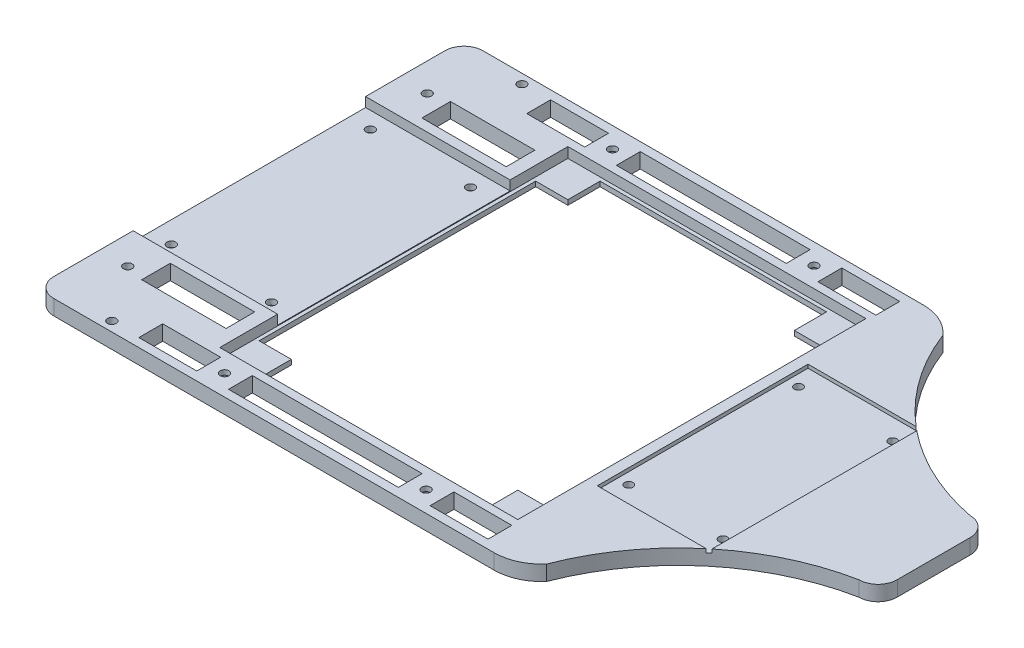
SolidWorks part; units mm, degrees
ref_plane "Alzado" through (0, 0, 0) normal (0, 0, 1) x (1, 0, 0)
ref_plane "Planta" through (0, 0, 0) normal (0, 1, 0) x (1, 0, 0)
ref_plane "Vista lateral" through (0, 0, 0) normal (1, 0, 0) x (0, 0, -1)
sketch "Croquis1" plane through (0, 0, 0) normal (0, 1, 0) x (1, 0, 0)
  line L1 (-363.842, 247.1559) -> (108.158, 247.1559) construction
  line L2 (98.4842, 266.9705) -> (494.4842, 266.9705) construction
  line L11 (99, 267.5) -> (495, 267.5) construction
  line L12 (0, 0) -> (200, 0)
  line L22 (0, 90) -> (105.7, 90)
  line L23 (105.7, 90) -> (105.7, 83.1308) construction
  line L24 (105.7, 83.1308) -> (120.7782, 83.1308) construction
  line L25 (200, 0) -> (200, 15.2)
  line L26 (200, 15.2) -> (191.999, 15.2) construction
  line L27 (191.999, 15.2) -> (191.999, 23.325) construction
  line L29 (0, 0) -> (-110.4, 0)
  line L30 (0, 90) -> (-79, 90)
  line L31 (-110.4, 0) -> (-110.4, 13.12)
  line L32 (-86.9998, 82.0528) -> (-86.9998, 41.494)
  arc A0 (105.7, 90) -> (120.7782, 83.1308) centre (105.672, 69.9553) cw
  arc A1 (200, 15.2) -> (191.999, 23.325) centre (192.001, 15.325) ccw
  arc A2 (120.7782, 83.1308) -> (191.999, 23.325) centre (210.4273, 117.5809) ccw
  arc A3 (-79, 90) -> (-86.9998, 82.0528) centre (-79, 82) ccw
  arc A4 (-110.4, 13.12) -> (-102.3535, 21.1199) centre (-102.4, 13.12) cw
  arc A5 (-102.3535, 21.1199) -> (-86.9998, 41.494) centre (-113.1395, 45.2203) ccw
  dimension "D6" = 20.0447
  dimension "D10" = 8
  dimension "D11" = 96.0405
  dimension "D15" = 8
  dimension "D17" = 8
  dimension "D19" = 26.4039
  dimension "D22" = 45.2203
  dimension "D1" = 90
  dimension "D2" = 200
  dimension "D3" = 105.7
  dimension "D4" = 6.8692
  dimension "D5" = 15.0782
  dimension "D7" = 15.2
  dimension "D8" = 8.001
  dimension "D9" = 8.125
  dimension "D12" = 105.7
  dimension "D13" = 310.4
  dimension "D14" = 79
  dimension "D16" = 13.12
  dimension "D18" = 40.5588
  dimension "D20" = 90
  dimension "D21" = 286.9998
extrude "Saliente-Extruir1" add sketch "Croquis1" along normal blind 6.35
mirror "Simetría2" about plane through (0, 6.35, 0) normal (0, 0, -1) of bodies 104
sketch "Croquis2" plane through (0, 6.35, 0) normal (0, 1, 0) x (1, 0, 0)
  line L0 (200, 0) -> (-110.4, 0) construction
  line L1 (200, -15.2) -> (200, 15.2) construction
  line L2 (-110.4, 13.12) -> (-110.4, -13.12) construction
  line L3 (0, 90) -> (-86.9348, 90) construction
  line L4 (105.7, 90) -> (-79, 90) construction
  line L5 (-17.875, 81.35) -> (70.325, 81.35) construction
  line L6 (0, 90) -> (0, 0) construction
  line L7 (-14.225, 81.35) -> (-1.9998, 81.35) construction
  line L8 (13.35, -90) -> (13.35, 90) construction
  line L9 (105.7, -90) -> (-79, -90) construction
  line L10 (-17.875, -81.35) -> (70.325, -81.35) construction
  line L15 (26.225, -81.35) -> (26.225, -54.2886) construction
  line L16 (-1.9998, -86.35) -> (61.85, -86.35)
  line L17 (-1.9998, -86.35) -> (-1.9998, -76.35)
  line L18 (-1.9998, -76.35) -> (61.85, -76.35)
  line L19 (61.85, -86.35) -> (61.85, -76.35)
  line L20 (-86.9998, -82.0528) -> (-86.9998, -41.494) construction
  line L21 (-46.9998, -76.35) -> (-22.7, -76.35)
  line L22 (-46.9998, -76.35) -> (-46.9998, -86.35)
  line L23 (-46.9998, -86.35) -> (-22.7, -86.35)
  line L24 (-22.7, -76.35) -> (-22.7, -86.35)
  line L25 (99.4498, -86.35) -> (75.15, -86.35)
  line L26 (75.15, -76.35) -> (75.15, -86.35)
  line L27 (99.4498, -76.35) -> (75.15, -76.35)
  line L28 (99.4498, -76.35) -> (99.4498, -86.35)
  line L29 (-46.9998, 86.35) -> (-22.7, 86.35)
  line L30 (-22.7, 76.35) -> (-22.7, 86.35)
  line L31 (-46.9998, 76.35) -> (-22.7, 76.35)
  line L32 (-46.9998, 76.35) -> (-46.9998, 86.35)
  line L33 (-1.9998, 76.35) -> (61.85, 76.35)
  line L34 (61.85, 86.35) -> (61.85, 76.35)
  line L35 (-1.9998, 86.35) -> (61.85, 86.35)
  line L36 (-1.9998, 86.35) -> (-1.9998, 76.35)
  line L37 (99.4498, 76.35) -> (99.4498, 86.35)
  line L38 (99.4498, 76.35) -> (75.15, 76.35)
  line L39 (75.15, 76.35) -> (75.15, 86.35)
  line L40 (99.4498, 86.35) -> (75.15, 86.35)
  circle A0 centre (68.5, 81.35) radius 1.825
  circle A1 centre (-16.05, 81.35) radius 1.825
  circle A2 centre (68.5, -81.35) radius 1.825
  circle A3 centre (-16.05, -81.35) radius 1.825
  point P33 (-1.9998, -81.35)
  point P41 (-22.7, -81.35)
  dimension "3.6" = 3.65
  dimension "D5" = 3.65
  dimension "D10" = 84.55
  dimension "D17" = 4.825
  dimension "D2" = 81.35
  dimension "D3" = 110.4
  dimension "D4" = 68.5
  dimension "D6" = 88.2
  dimension "D7" = 63.8498
  dimension "D8" = 6.65
  dimension "D9" = 10
  dimension "D11" = 14.0502
  dimension "D12" = 6.65
  dimension "D13" = 10
  dimension "D14" = 40
  dimension "D15" = 90
  dimension "D16" = 90
  dimension "D18" = 88.2
extrude "Cortar-Extruir1" cut sketch "Croquis2" against normal through all
sketch "Croquis4" plane through (0, 6.35, 0) normal (0, 1, 0) x (1, 0, 0)
  line L0 (200, 0) -> (-110.4, 0) construction
  line L1 (200, -15.2) -> (200, 15.2) construction
  line L2 (-110.4, 13.12) -> (-110.4, -13.12) construction
  line L4 (105, 42.05) -> (150, 42.05)
  line L5 (105, 42.05) -> (105, -42.05)
  line L6 (105, -42.05) -> (150, -42.05)
  line L7 (150, 42.05) -> (150, -42.05)
  point P10 (150, 0)
  dimension "D1" = 84.1
  dimension "D2" = 45
  dimension "D3" = 50
extrude "Cortar-Extruir3" cut sketch "Croquis4" against normal blind 1.5
sketch "Croquis5" plane through (0, 4.85, 0) normal (0, 1, 0) x (1, 0, 0)
  line L0 (127.5, 42.05) -> (127.5, -42.05) construction
  line L1 (150, 42.05) -> (105, 42.05) construction
  line L2 (105, -42.05) -> (150, -42.05) construction
  line L3 (105, 0) -> (150, 0) construction
  line L4 (105, 42.05) -> (105, -42.05) construction
  line L5 (150, -42.05) -> (150, 42.05) construction
  line L7 (147.25, 37.35) -> (147.25, 42.05) construction
  line L8 (149, 35.6) -> (150, 35.6) construction
  line L9 (107.75, -37.35) -> (105, -37.35) construction
  line L10 (107.75, 37.35) -> (105, 37.35) construction
  line L11 (105, 42.05) -> (105, -42.05) construction
  line L12 (106, -35.6) -> (149, -35.6) construction
  circle A4 centre (147.25, 35.6) radius 1.75 construction
  circle A5 centre (147.25, 35.6) radius 1.75
  circle A6 centre (107.75, 35.6) radius 1.75
  circle A7 centre (147.25, -35.6) radius 1.75
  circle A8 centre (107.75, -35.6) radius 1.75
  dimension "D1" = 3.5
  dimension "D4" = 74.7
  dimension "D2" = 4.7
  dimension "D3" = 1
extrude "Cortar-Extruir4" cut sketch "Croquis5" against normal through all
sketch "Croquis7" plane through (0, 6.35, 0) normal (0, 1, 0) x (1, 0, 0)
  line L2 (107.925, 39.325) -> (107.925, 44.325) construction
  line L3 (105, 42.05) -> (150, 42.05)
  line L4 (105, 42.05) -> (105, 44.325)
  line L5 (105, 44.325) -> (150, 44.325)
  line L6 (150, 42.05) -> (150, 44.325)
  line L7 (150, -42.05) -> (150, 42.05) construction
  dimension "D2" = 5
  dimension "D3" = 5
  dimension "D4" = 2.275
extrude "Cortar-Extruir5" cut sketch "Croquis7" against normal up to surface (1.5 mm away) up to face at (107.75, 4.85, -37.35)
sketch "Croquis9" plane through (0, 6.35, 0) normal (0, 1, 0) x (1, 0, 0)
  line L0 (-110.4, 0) -> (200, 0) construction
  line L1 (-110.4, 13.12) -> (-110.4, -13.12) construction
  line L2 (200, -15.2) -> (200, 15.2) construction
  line L3 (-26.3998, 76.35) -> (-26.3998, -76.35) construction
  line L4 (-26.3998, 73) -> (98.6002, 73)
  line L5 (-26.3998, 73) -> (-26.3998, -73)
  line L6 (-26.3998, -73) -> (98.6002, -73)
  line L7 (98.6002, 73) -> (98.6002, -73)
  line L8 (-46.9998, 76.35) -> (-22.7, 76.35) construction
  line L9 (-22.7, -76.35) -> (-46.9998, -76.35) construction
  point P10 (98.6002, 0)
  dimension "D1" = 125
  dimension "D2" = 146
  dimension "D3" = 101.3998
extrude "Cortar-Extruir7" cut sketch "Croquis9" against normal blind 4.3
sketch "Croquis10" plane through (0, 0, 0) normal (0, -1, 0) x (1, 0, 0)
  line L0 (200, 0) -> (-110.4, 0) construction
  line L1 (200, 15.2) -> (200, -15.2) construction
  line L2 (-110.4, -13.12) -> (-110.4, 13.12) construction
  line L3 (105.7, 90) -> (-79, 90) construction
  line L4 (29.9251, 90) -> (29.9251, 0) construction
  line L5 (-16.05, 81.35) -> (68.5, 81.35) construction
  line L6 (26.225, 81.35) -> (26.225, 0) construction
  circle A0 centre (-16.05, 81.35) radius 2.8
  circle A3 centre (-16.05, -81.35) radius 2.8
  circle A4 centre (68.5, -81.35) radius 2.8
  circle A5 centre (68.5, 81.35) radius 2.8
  dimension "D3" = 5.6
  dimension "D1" = 90
  dimension "D2" = 170.0749
extrude "Cortar-Extruir8" cut sketch "Croquis10" against normal blind 4.35
sketch "Croquis16" plane through (0, 6.35, 0) normal (0, 1, 0) x (1, 0, 0)
  line L0 (-86.9998, 41.494) -> (-110.4, 41.494)
  line L1 (-110.4, 41.494) -> (-110.4, 13.12)
  line L2 (-110.4, 13.12) -> (-110.4, -13.12)
  line L3 (-110.4, -13.12) -> (-110.4, -41.494)
  line L4 (-110.4, -41.494) -> (-86.9998, -41.494)
  line L5 (-86.9998, -41.494) -> (-86.9998, 41.494)
extrude "Cortar-Extruir12" cut sketch "Croquis16" against normal through all
sketch "Croquis18" plane through (0, 6.35, 0) normal (0, 1, 0) x (1, 0, 0)
  line L0 (105, 44.325) -> (103, 44.325)
  line L1 (103, 44.325) -> (103, -44.05)
  line L2 (103, -44.05) -> (150, -44.05)
  line L3 (150, -44.05) -> (150, -42.05)
  line L4 (150, -42.05) -> (105, -42.05)
  line L5 (105, -42.05) -> (105, 44.325)
  dimension "D1" = 2
  dimension "D2" = 2
extrude "Cortar-Extruir15" cut sketch "Croquis18" against normal up to surface (1.5 mm away) up to face at (107.75, 4.85, -37.35)
sketch "Croquis19" plane through (0, 6.35, 0) normal (0, 1, 0) x (1, 0, 0)
  line L0 (200, 0) -> (-86.9998, 0) construction
  line L1 (200, -15.2) -> (200, 15.2) construction
  line L2 (-86.9998, 82.0528) -> (-86.9998, -82.0528) construction
  line L3 (-17.875, 81.35) -> (-22.7, 81.35) construction
  line L4 (-22.7, 76.35) -> (-22.7, 86.35) construction
  line L5 (-9.395, 81.35) -> (-14.225, 81.35) construction
  line L6 (-1.9998, 86.35) -> (-9.395, 86.35)
  line L7 (-1.9998, 86.35) -> (-1.9998, 76.35)
  line L8 (-1.9998, 76.35) -> (-9.395, 76.35)
  line L9 (-9.395, 86.35) -> (-9.395, 76.35)
  line L10 (-1.9998, -76.35) -> (-9.395, -76.35)
  line L11 (-9.395, -86.35) -> (-9.395, -76.35)
  line L12 (-1.9998, -86.35) -> (-9.395, -86.35)
  line L13 (-1.9998, -86.35) -> (-1.9998, -76.35)
  circle A0 centre (-16.05, 81.35) radius 1.825 construction
  dimension "D1" = 4.83
extrude "Cortar-Extruir16" cut sketch "Croquis19" against normal through all
sketch "Croquis20" plane through (0, 6.35, 0) normal (0, 1, 0) x (1, 0, 0)
  line L0 (-86.9998, 0) -> (-26.3998, 0) construction
  line L1 (-86.9998, 82.0528) -> (-86.9998, -82.0528) construction
  line L2 (-26.3998, 73) -> (-26.3998, -73) construction
  line L8 (-86.9998, 48.75) -> (-26.3998, 48.75)
  line L9 (-86.9998, 48.75) -> (-86.9998, -48.75)
  line L10 (-86.9998, -48.75) -> (-26.3998, -48.75)
  line L11 (-26.3998, 48.75) -> (-26.3998, -48.75)
  point P11 (-56.6998, 48.75)
  point P12 (-56.6998, 0)
  point P13 (-86.9998, 0)
  dimension "D1" = 97.5
extrude "Cortar-Extruir17" cut sketch "Croquis20" against normal blind 4
sketch "Croquis21" plane through (0, 2.35, 0) normal (0, 1, 0) x (1, 0, 0)
  line L0 (-56.9998, 48.75) -> (-56.9998, -48.75) construction
  line L2 (-86.9998, 0) -> (-56.9998, 0) construction
  line L3 (-86.9998, -48.75) -> (-26.3998, -48.75) construction
  line L4 (-26.3998, 48.75) -> (-86.9998, 48.75) construction
  line L5 (-86.9998, 82.0528) -> (-86.9998, 48.75) construction
  line L6 (-86.9998, 48.75) -> (-86.9998, -48.75) construction
  circle A0 centre (-77.9998, 41.75) radius 1.825
  circle A1 centre (-35.9998, 41.75) radius 1.825
  circle A2 centre (-35.9998, -41.75) radius 1.825
  circle A3 centre (-77.9998, -41.75) radius 1.825
  dimension "D1" = 3.65
  dimension "D2" = 30
  dimension "D3" = 48.75
  dimension "D4" = 9
  dimension "D5" = 7
extrude "Cortar-Extruir18" cut sketch "Croquis21" against normal through all
sketch "Croquis25" plane through (0, 0, 0) normal (0, -1, 0) x (1, 0, 0)
  line L0 (-86.9998, 0) -> (0, 0) construction
  line L1 (-86.9998, -82.0528) -> (-86.9998, 82.0528) construction
  line L2 (-67.3998, -58.76) -> (-31.9998, -58.76) construction
  line L4 (-67.3998, 64.76) -> (-31.9998, 64.76)
  line L5 (-31.9998, 52.76) -> (-31.9998, 64.76)
  line L6 (-67.3998, -64.76) -> (-31.9998, -64.76) construction
  line L8 (-67.3998, -52.76) -> (-31.9998, -52.76)
  line L9 (-67.3998, -52.76) -> (-67.3998, -64.76)
  line L10 (-67.3998, -64.76) -> (-31.9998, -64.76)
  line L11 (-31.9998, -52.76) -> (-31.9998, -64.76)
  line L15 (-67.3998, 52.76) -> (-31.9998, 52.76)
  line L16 (-67.3998, 52.76) -> (-67.3998, 64.76)
  line L17 (105.7, -90) -> (-79, -90) construction
  point P16 (-67.3998, -58.76)
  dimension "D1" = 55
  dimension "D2" = 55
  dimension "D3" = 12
  dimension "D4" = 19.6
  dimension "D5" = 31.24
extrude "Cortar-Extruir21" cut sketch "Croquis25" against normal through all
sketch "Croquis26" plane through (0, 2.05, 0) normal (0, 1, 0) x (1, 0, 0)
  line L0 (-11.3998, 71.5) -> (-11.3998, 58)
  line L1 (-11.3998, 58) -> (-24.8998, 58)
  line L2 (-24.8998, 58) -> (-24.8998, -58)
  line L3 (-24.8998, -58) -> (-11.3998, -58)
  line L4 (-11.3998, -58) -> (-11.3998, -71.5)
  line L5 (-11.3998, -71.5) -> (83.6002, -71.5)
  line L6 (83.6002, -71.5) -> (83.6002, -58)
  line L7 (83.6002, -58) -> (97.1002, -58)
  line L8 (97.1002, -58) -> (97.1002, 58)
  line L9 (97.1002, 58) -> (83.6002, 58)
  line L10 (83.6002, 58) -> (83.6002, 71.5)
  line L11 (83.6002, 71.5) -> (-11.3998, 71.5)
  line L12 (-26.3998, 73) -> (-26.3998, 48.75) construction
  line L13 (98.6002, 73) -> (-26.3998, 73) construction
  line L14 (98.6002, -73) -> (98.6002, 73) construction
  line L15 (-26.3998, -73) -> (98.6002, -73) construction
  line L16 (98.6002, -73) -> (98.6002, 73) construction
  line L17 (-26.3998, -73) -> (98.6002, -73) construction
  line L18 (-26.3998, -48.75) -> (-26.3998, -73) construction
  line L19 (-26.3998, -48.75) -> (-26.3998, 48.75) construction
  dimension "D1" = 15
  dimension "D2" = 15
  dimension "D3" = 15
  dimension "D4" = 15
  dimension "D5" = 15
  dimension "D6" = 15
  dimension "D7" = 15
  dimension "D8" = 15
  dimension "D9" = 1.5
  dimension "D10" = 1.5
  dimension "D11" = 1.5
  dimension "D12" = 1.5
extrude "Cortar-Extruir22" cut sketch "Croquis26" against normal through all
sketch "Croquis28" plane through (0, 6.35, 0) normal (0, 1, 0) x (1, 0, 0)
  line L0 (0, 0) -> (200, 0) construction
  line L1 (200, -15.2) -> (200, 15.2) construction
  line L2 (-86.9998, -48.75) -> (-86.9998, -82.0528) construction
  line L3 (-86.9998, -48.75) -> (-26.3998, -48.75) construction
  line L4 (105.7, -90) -> (-79, -90) construction
  circle A0 centre (-75.1998, -62.81) radius 1.825
  circle A1 centre (-58.6998, -86) radius 1.825
  circle A2 centre (-75.1998, 62.81) radius 1.825
  circle A3 centre (-58.6998, 86) radius 1.825
  dimension "D3" = 3.65
  dimension "D6" = 3.65
  dimension "D1" = 11.8
  dimension "D2" = 14.06
  dimension "D4" = 4
  dimension "D5" = 28.3
extrude "Cortar-Extruir24" cut sketch "Croquis28" against normal through all
